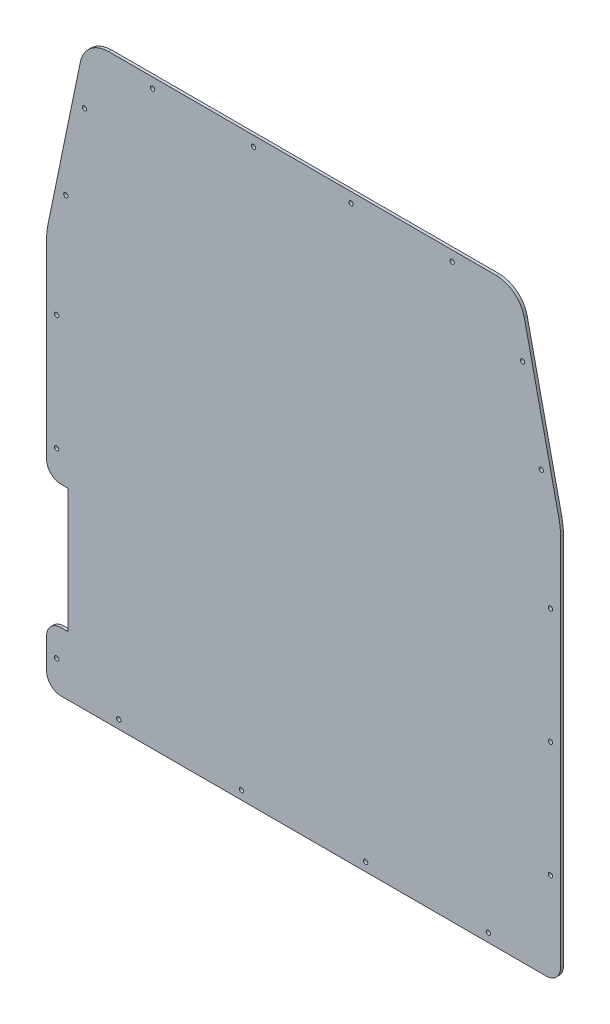
SolidWorks part; units mm, degrees
ref_plane "Front Plane" through (0, 0, 0) normal (0, 0, 1) x (1, 0, 0)
ref_plane "Top Plane" through (0, 0, 0) normal (0, 1, 0) x (1, 0, 0)
ref_plane "Right Plane" through (0, 0, 0) normal (1, 0, 0) x (0, 0, -1)
sketch "Sketch1" plane through (0, 0, -1267.1075) normal (0, 0, 1) x (1, 0, 0)
  line L0 (36.1461, 1376.3064) -> (13.7654, 1267.8705) construction
  line L1 (12.7333, 1257.7637) -> (12.7333, 1126.2637) construction
  line L2 (22.7333, 1116.2637) -> (27.7333, 1116.2637) construction
  line L3 (22.7333, 1030.2637) -> (27.7333, 1030.2637) construction
  line L4 (12.7333, 1020.2637) -> (12.7333, 999.2637) construction
  line L5 (22.7333, 989.2637) -> (358.7333, 989.2637) construction
  line L6 (368.7333, 999.2637) -> (368.7333, 1257.7662) construction
  line L7 (343.6552, 1376.584) -> (367.5527, 1268.5669) construction
  line L8 (324.1274, 1392.2637) -> (55.7333, 1392.2637) construction
  line L9 (36.1461, 1376.3064) -> (13.7654, 1267.8705)
  line L10 (12.7333, 1257.7637) -> (12.7333, 1126.2637)
  line L11 (22.7333, 1116.2637) -> (27.7333, 1116.2637)
  line L12 (22.7333, 1030.2637) -> (27.7333, 1030.2637)
  line L13 (12.7333, 1020.2637) -> (12.7333, 999.2637)
  line L14 (22.7333, 989.2637) -> (358.7333, 989.2637)
  line L15 (368.7333, 999.2637) -> (368.7333, 1257.7662)
  line L16 (343.6552, 1376.584) -> (367.5527, 1268.5669)
  line L17 (324.1274, 1392.2637) -> (55.7333, 1392.2637)
  line L18 (27.7333, 1116.2637) -> (27.7333, 1030.2637)
  arc A0 (55.7333, 1392.2637) -> (36.1461, 1376.3064) centre (55.7333, 1372.2637) ccw construction
  arc A1 (13.7654, 1267.8705) -> (12.7333, 1257.7637) centre (62.7333, 1257.7637) ccw construction
  arc A2 (12.7333, 1126.2637) -> (22.7333, 1116.2637) centre (22.7333, 1126.2637) ccw construction
  arc A3 (22.7333, 1030.2637) -> (12.7333, 1020.2637) centre (22.7333, 1020.2637) ccw construction
  arc A4 (12.7333, 999.2637) -> (22.7333, 989.2637) centre (22.7333, 999.2637) ccw construction
  arc A5 (358.7333, 989.2637) -> (368.7333, 999.2637) centre (358.7333, 999.2637) ccw construction
  arc A6 (368.7333, 1257.7662) -> (367.5527, 1268.5669) centre (318.7333, 1257.7662) ccw construction
  arc A7 (343.6552, 1376.584) -> (324.1274, 1392.2637) centre (324.1274, 1372.2637) ccw construction
  arc A8 (55.7333, 1392.2637) -> (36.1461, 1376.3064) centre (55.7333, 1372.2637) ccw
  arc A9 (13.7654, 1267.8705) -> (12.7333, 1257.7637) centre (62.7333, 1257.7637) ccw
  arc A10 (12.7333, 1126.2637) -> (22.7333, 1116.2637) centre (22.7333, 1126.2637) ccw
  arc A11 (22.7333, 1030.2637) -> (12.7333, 1020.2637) centre (22.7333, 1020.2637) ccw
  arc A12 (12.7333, 999.2637) -> (22.7333, 989.2637) centre (22.7333, 999.2637) ccw
  arc A13 (358.7333, 989.2637) -> (368.7333, 999.2637) centre (358.7333, 999.2637) ccw
  arc A14 (368.7333, 1257.7662) -> (367.5527, 1268.5669) centre (318.7333, 1257.7662) ccw
  arc A15 (343.6552, 1376.584) -> (324.1274, 1392.2637) centre (324.1274, 1372.2637) ccw
  circle A16 centre (19.7333, 1010.2637) radius 1.5 construction
  circle A17 centre (62.7333, 995.2637) radius 1.5 construction
  circle A18 centre (147.7333, 995.2637) radius 1.5 construction
  circle A19 centre (233.7333, 995.2637) radius 1.5 construction
  circle A20 centre (318.7333, 995.2637) radius 1.5 construction
  circle A21 centre (361.7333, 1051.2637) radius 1.5 construction
  circle A22 centre (361.7333, 1131.2637) radius 1.5 construction
  circle A23 centre (361.7333, 1211.2637) radius 1.5 construction
  circle A24 centre (355.3621, 1291.2637) radius 1.5 construction
  circle A25 centre (342.4011, 1349.8471) radius 1.5 construction
  circle A26 centre (293.6552, 1385.2637) radius 1.5 construction
  circle A27 centre (223.6552, 1385.2637) radius 1.5 construction
  circle A28 centre (156.1461, 1385.2637) radius 1.5 construction
  circle A29 centre (86.1461, 1385.2637) radius 1.5 construction
  circle A30 centre (39.0654, 1349.8471) radius 1.5 construction
  circle A31 centre (26.1044, 1291.2637) radius 1.5 construction
  circle A32 centre (19.7333, 1216.2637) radius 1.5 construction
  circle A33 centre (19.7333, 1136.2637) radius 1.5 construction
  circle A34 centre (19.7333, 1010.2637) radius 1.5
  circle A35 centre (62.7333, 995.2637) radius 1.5
  circle A36 centre (147.7333, 995.2637) radius 1.5
  circle A37 centre (233.7333, 995.2637) radius 1.5
  circle A38 centre (318.7333, 995.2637) radius 1.5
  circle A39 centre (361.7333, 1051.2637) radius 1.5
  circle A40 centre (361.7333, 1131.2637) radius 1.5
  circle A41 centre (361.7333, 1211.2637) radius 1.5
  circle A42 centre (355.3621, 1291.2637) radius 1.5
  circle A43 centre (342.4011, 1349.8471) radius 1.5
  circle A44 centre (293.6552, 1385.2637) radius 1.5
  circle A45 centre (223.6552, 1385.2637) radius 1.5
  circle A46 centre (156.1461, 1385.2637) radius 1.5
  circle A47 centre (86.1461, 1385.2637) radius 1.5
  circle A48 centre (39.0654, 1349.8471) radius 1.5
  circle A49 centre (26.1044, 1291.2637) radius 1.5
  circle A50 centre (19.7333, 1216.2637) radius 1.5
  circle A51 centre (19.7333, 1136.2637) radius 1.5
extrude "Boss-Extrude1" add sketch "Sketch1" along normal blind 2
